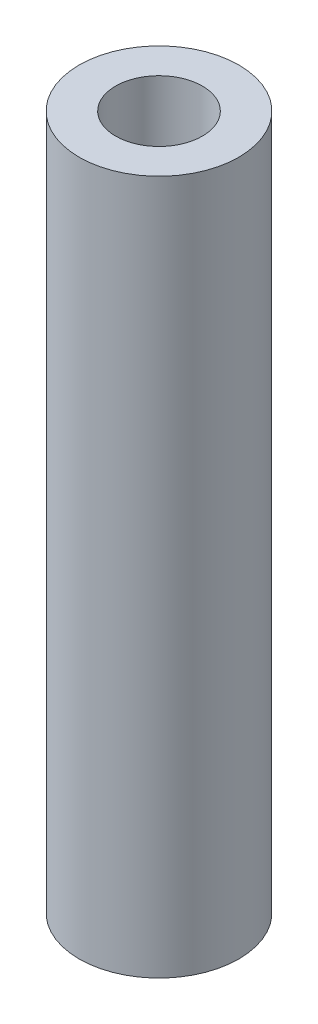
SolidWorks part; units mm, degrees
ref_plane "前视基准面" through (0, 0, 0) normal (0, 0, 1) x (1, 0, 0)
ref_plane "上视基准面" through (0, 0, 0) normal (0, 1, 0) x (1, 0, 0)
ref_plane "右视基准面" through (0, 0, 0) normal (1, 0, 0) x (0, 0, -1)
sketch "草图1" plane through (0, 0, 0) normal (0, 1, 0) x (1, 0, 0)
  circle A0 centre (0, 0) radius 1.25
  circle A1 centre (0, 0) radius 2.3
  dimension "D1" = 2.5
  dimension "D2" = 4.6
extrude "凸台-拉伸1" add sketch "草图1" along normal blind 20
